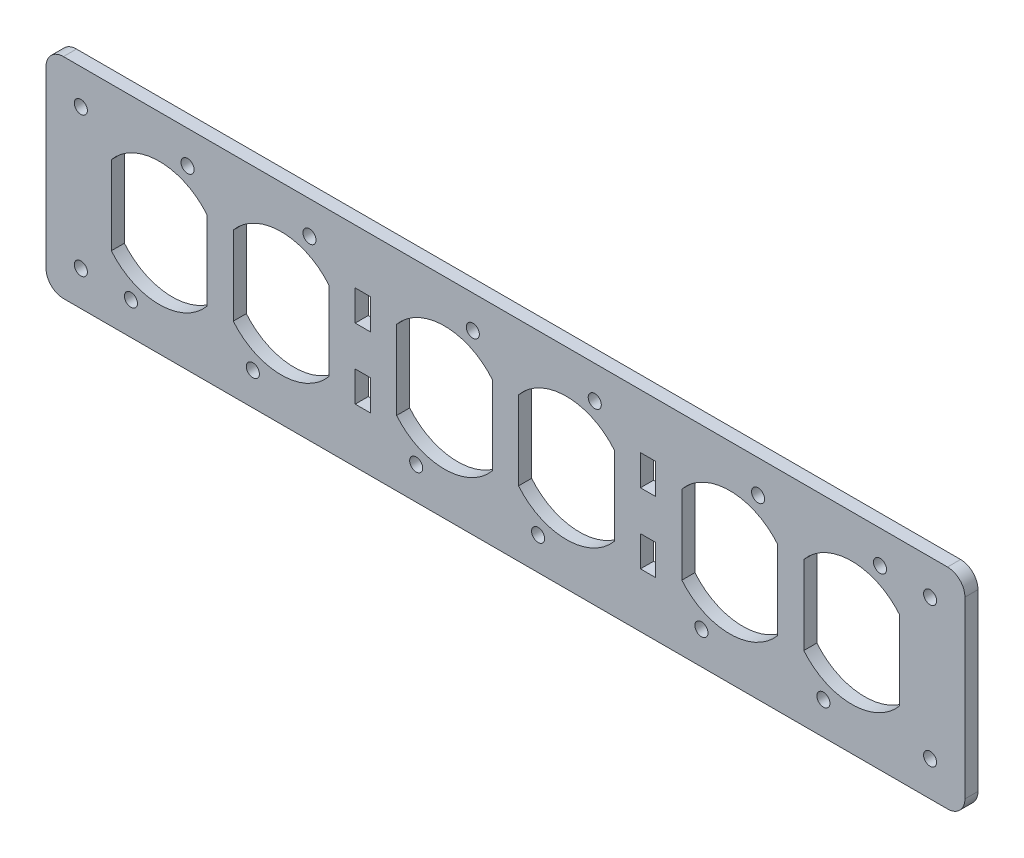
SolidWorks part; units mm, degrees
ref_plane "Front Plane" through (0, 0, 0) normal (0, 0, 1) x (1, 0, 0)
ref_plane "Top Plane" through (0, 0, 0) normal (0, 1, 0) x (1, 0, 0)
ref_plane "Right Plane" through (0, 0, 0) normal (1, 0, 0) x (0, 0, -1)
sketch "Sketch1" plane through (0, 0, 0) normal (0, 0, 1) x (1, 0, 0)
  line L0 (15, 15) -> (15, 33.1177)
  line L5 (43, 15) -> (43, 33.1177)
  line L6 (65, 15) -> (65, 33.1177)
  line L7 (37, 15) -> (37, 33.1177)
  line L8 (15, 9.8088) -> (37, 38.3088) construction
  line L9 (15, 38.3088) -> (37, 9.8088) construction
  line L10 (43, 9.8088) -> (65, 38.3088) construction
  line L11 (43, 38.3088) -> (65, 9.8088) construction
  line L12 (80.5, 15) -> (80.5, 33.1177)
  line L13 (71, 35.6177) -> (74.5, 35.6177)
  line L14 (71, 35.6177) -> (71, 28.6177)
  line L15 (71, 28.6177) -> (74.5, 28.6177)
  line L16 (74.5, 35.6177) -> (74.5, 28.6177)
  line L17 (71, 35.6177) -> (74.5, 28.6177) construction
  line L18 (71, 28.6177) -> (74.5, 35.6177) construction
  line L19 (71, 19.5) -> (74.5, 19.5)
  line L20 (71, 19.5) -> (71, 12.5)
  line L21 (71, 12.5) -> (74.5, 12.5)
  line L22 (74.5, 19.5) -> (74.5, 12.5)
  line L23 (71, 19.5) -> (74.5, 12.5) construction
  line L24 (71, 12.5) -> (74.5, 19.5) construction
  line L25 (102.5, 15) -> (102.5, 33.1177)
  line L26 (80.5, 9.8088) -> (102.5, 38.3088) construction
  line L27 (80.5, 38.3088) -> (102.5, 9.8088) construction
  line L28 (108.5, 15) -> (108.5, 33.1177)
  line L29 (130.5, 15) -> (130.5, 33.1177)
  line L30 (108.5, 9.8088) -> (130.5, 38.3088) construction
  line L31 (108.5, 38.3088) -> (130.5, 9.8088) construction
  line L32 (146, 15) -> (146, 33.1177)
  line L33 (4, 0) -> (207, 0)
  line L34 (0, 4) -> (0, 44.1177)
  line L35 (4, 48.1177) -> (207, 48.1177)
  line L36 (211, 4) -> (211, 44.1177)
  line L37 (0, 0) -> (211, 48.1177) construction
  line L38 (0, 48.1177) -> (211, 0) construction
  line L39 (136.5, 35.6177) -> (140, 35.6177)
  line L40 (136.5, 35.6177) -> (136.5, 28.6177)
  line L41 (136.5, 28.6177) -> (140, 28.6177)
  line L42 (140, 35.6177) -> (140, 28.6177)
  line L43 (136.5, 35.6177) -> (140, 28.6177) construction
  line L44 (136.5, 28.6177) -> (140, 35.6177) construction
  line L45 (136.5, 19.5) -> (140, 19.5)
  line L46 (136.5, 19.5) -> (136.5, 12.5)
  line L47 (136.5, 12.5) -> (140, 12.5)
  line L48 (140, 19.5) -> (140, 12.5)
  line L49 (136.5, 19.5) -> (140, 12.5) construction
  line L50 (136.5, 12.5) -> (140, 19.5) construction
  line L51 (168, 15) -> (168, 33.1177)
  line L52 (146, 9.8088) -> (168, 38.3088) construction
  line L53 (146, 38.3088) -> (168, 9.8088) construction
  line L54 (174, 15) -> (174, 33.1177)
  line L55 (196, 15) -> (196, 33.1177)
  line L56 (174, 9.8088) -> (196, 38.3088) construction
  line L57 (174, 38.3088) -> (196, 9.8088) construction
  arc A0 (37, 33.1177) -> (15, 33.1177) centre (26, 24.0588) ccw
  arc A1 (15, 15) -> (37, 15) centre (26, 24.0588) ccw
  circle A2 centre (32.5, 40.6177) radius 1.5
  circle A3 centre (19.5, 7.5) radius 1.5
  arc A4 (65, 33.1177) -> (43, 33.1177) centre (54, 24.0588) ccw
  arc A5 (43, 15) -> (65, 15) centre (54, 24.0588) ccw
  circle A6 centre (60.5, 40.6177) radius 1.5
  circle A7 centre (47.5, 7.5) radius 1.5
  arc A8 (102.5, 33.1177) -> (80.5, 33.1177) centre (91.5, 24.0588) ccw
  arc A9 (80.5, 15) -> (102.5, 15) centre (91.5, 24.0588) ccw
  circle A10 centre (98, 40.6177) radius 1.5
  circle A11 centre (85, 7.5) radius 1.5
  arc A12 (130.5, 33.1177) -> (108.5, 33.1177) centre (119.5, 24.0588) ccw
  arc A13 (108.5, 15) -> (130.5, 15) centre (119.5, 24.0588) ccw
  circle A14 centre (126, 40.6177) radius 1.5
  circle A15 centre (113, 7.5) radius 1.5
  circle A16 centre (8, 40.1177) radius 1.5
  circle A17 centre (8, 8) radius 1.5
  circle A18 centre (203, 8) radius 1.5
  circle A19 centre (203, 40.1177) radius 1.5
  arc A20 (168, 33.1177) -> (146, 33.1177) centre (157, 24.0588) ccw
  arc A21 (146, 15) -> (168, 15) centre (157, 24.0588) ccw
  circle A22 centre (163.5, 40.6177) radius 1.5
  circle A23 centre (150.5, 7.5) radius 1.5
  arc A24 (196, 33.1177) -> (174, 33.1177) centre (185, 24.0588) ccw
  arc A25 (174, 15) -> (196, 15) centre (185, 24.0588) ccw
  circle A26 centre (191.5, 40.6177) radius 1.5
  circle A27 centre (178.5, 7.5) radius 1.5
  arc A28 (207, 48.1177) -> (211, 44.1177) centre (207, 44.1177) cw
  arc A29 (207, 0) -> (211, 4) centre (207, 4) ccw
  arc A30 (4, 0) -> (0, 4) centre (4, 4) cw
  arc A31 (0, 44.1177) -> (4, 48.1177) centre (4, 44.1177) cw
  point P10 (26, 24.0588)
  point P16 (26, 9.8088)
  point P22 (54, 24.0588)
  point P34 (72.75, 32.1177)
  point P39 (72.75, 16)
  point P40 (195.8032, -5.5206)
  point P45 (91.5, 24.0588)
  point P51 (91.5, 9.8088)
  point P62 (119.5, 24.0588)
  point P68 (119.5, 9.8088)
  point P75 (105.5, 24.0588)
  point P88 (138.25, 32.1177)
  point P93 (138.25, 16)
  point P98 (157, 24.0588)
  point P104 (157, 9.8088)
  point P113 (185, 24.0588)
  point P119 (185, 9.8088)
  point P124 (0, 0)
  point P125 (208.682, 11.3663)
  dimension "D7" = 3
  dimension "D8" = 4.5
  dimension "D9" = 7.5
  dimension "D10" = 3
  dimension "D28" = 3
  dimension "D31" = 3
  dimension "D46" = 3
  dimension "D49" = 3
  dimension "D55" = 3
  dimension "D58" = 3
  dimension "D61" = 3
  dimension "D72" = 3
  dimension "D75" = 3
  dimension "D86" = 3
  dimension "D89" = 3
  dimension "D96" = 3
  dimension "D100" = 4
  dimension "D2" = 2
  dimension "D3" = 22
  dimension "D4" = 28.5
  dimension "D5" = 5.1912
  dimension "D6" = 11
  dimension "D11" = 4.5
  dimension "D12" = 3.5
  dimension "D13" = 7
  dimension "D14" = 11
  dimension "D15" = 9.0588
  dimension "D16" = 22
  dimension "D17" = 7.5
  dimension "D18" = 6
  dimension "D19" = 2.5
  dimension "D20" = 2.5
  dimension "D21" = 22
  dimension "D22" = 28.5
  dimension "D23" = 5.1912
  dimension "D24" = 11
  dimension "D25" = 11
  dimension "D26" = 9.0588
  dimension "D27" = 22
  dimension "D29" = 4.5
  dimension "D30" = 7.5
  dimension "D32" = 4.5
  dimension "D33" = 7.5
  dimension "D34" = 6
  dimension "D35" = 15
  dimension "D36" = 15
  dimension "D37" = 6
  dimension "D38" = 6
  dimension "D39" = 22
  dimension "D40" = 28.5
  dimension "D41" = 5.1912
  dimension "D42" = 11
  dimension "D43" = 11
  dimension "D44" = 9.0588
  dimension "D45" = 22
  dimension "D47" = 4.5
  dimension "D48" = 7.5
  dimension "D50" = 4.5
  dimension "D51" = 7.5
  dimension "D52" = 6
  dimension "D53" = 3.5
  dimension "D54" = 15
  dimension "D56" = 8
  dimension "D57" = 8
  dimension "D59" = 8
  dimension "D60" = 8
  dimension "D62" = 8
  dimension "D63" = 8
  dimension "D64" = 7
  dimension "D65" = 22
  dimension "D66" = 28.5
  dimension "D67" = 5.1912
  dimension "D68" = 11
  dimension "D69" = 11
  dimension "D70" = 9.0588
  dimension "D71" = 22
  dimension "D73" = 4.5
  dimension "D74" = 7.5
  dimension "D76" = 4.5
  dimension "D77" = 7.5
  dimension "D78" = 6
  dimension "D79" = 22
  dimension "D80" = 28.5
  dimension "D81" = 5.1912
  dimension "D82" = 11
  dimension "D83" = 11
  dimension "D84" = 9.0588
  dimension "D85" = 22
  dimension "D87" = 4.5
  dimension "D88" = 7.5
  dimension "D90" = 4.5
  dimension "D91" = 7.5
  dimension "D92" = 6
  dimension "D93" = 6
  dimension "D94" = 2.5
  dimension "D95" = 2.5
  dimension "D97" = 8
  dimension "D98" = 8
  dimension "D99" = 15
extrude "Boss-Extrude1" add sketch "Sketch1" along normal blind 3
